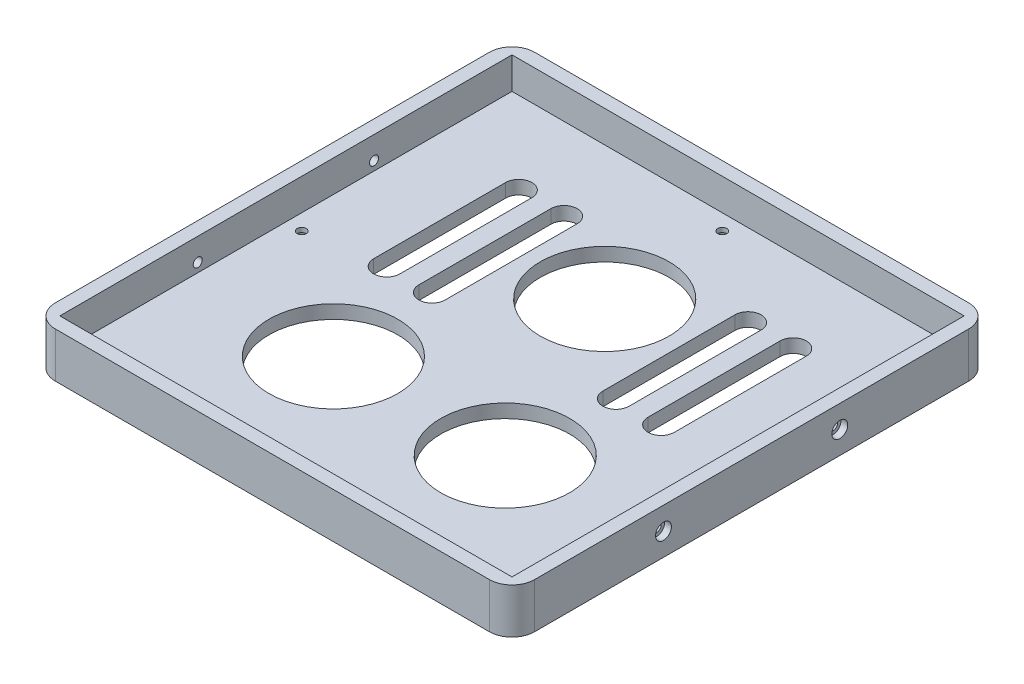
SolidWorks part; units mm, degrees
ref_plane "Front Plane" through (0, 0, 0) normal (0, 0, 1) x (1, 0, 0)
ref_plane "Top Plane" through (0, 0, 0) normal (0, 1, 0) x (1, 0, 0)
ref_plane "Right Plane" through (0, 0, 0) normal (1, 0, 0) x (0, 0, -1)
sketch "Sketch1" plane through (0, 0, 0) normal (0, 1, 0) x (1, 0, 0)
  line L1 (-53, 53) -> (53, 53)
  line L2 (-53, 53) -> (-53, -53)
  line L3 (-53, -53) -> (53, -53)
  line L4 (53, 53) -> (53, -53)
  line L5 (-53, 53) -> (53, -53) construction
  line L6 (-53, -53) -> (53, 53) construction
  point P0 (0, 0)
  dimension "D1" = 106
  dimension "D2" = 106
extrude "Boss-Extrude1" add sketch "Sketch1" along normal blind 10
sketch "Sketch3" plane through (0, 10, 0) normal (0, 1, 0) x (1, 0, 0)
  line L5 (-50, 50) -> (50, 50)
  line L6 (-50, 50) -> (-50, -50)
  line L7 (-50, -50) -> (50, -50)
  line L8 (50, 50) -> (50, -50)
  point P0 (0, 0)
  point P6 (0, 0)
extrude "Cut-Extrude5" cut sketch "Sketch3" against normal blind 7
sketch "Sketch7" plane through (0, 3, 0) normal (0, 1, 0) x (1, 0, 0)
  line L0 (0, 49) -> (0, 20.5) construction
  line L1 (-49, 49) -> (49, 49) construction
  line L2 (-49, 49) -> (-49, -49) construction
  line L3 (-49, -49) -> (49, -49) construction
  line L4 (49, 49) -> (49, -49) construction
  line L5 (0, -49) -> (0, -20.5) construction
  line L6 (49, -20.5) -> (19, -20.5)
  circle A0 centre (0, 20.5) radius 14.25
  circle A1 centre (19, -20.5) radius 14.25
  circle A2 centre (-19, -20.5) radius 14.25
  point P0 (0, 0)
  dimension "D1" = 28.5
  dimension "D2" = 28.5
extrude "Cut-Extrude6" cut sketch "Sketch7" against normal blind 7
sketch "Sketch8" plane through (0, 3, 0) normal (0, 1, 0) x (1, 0, 0)
  line L1 (-49, 49) -> (49, 49) construction
  line L2 (-49, 49) -> (-49, -49) construction
  line L3 (-49, -49) -> (49, -49) construction
  line L4 (49, 49) -> (49, -49) construction
  point P0 (0, 0)
  dimension "D1" = 98
  dimension "D2" = 98
sketch "Sketch9" plane through (0, 0, 0) normal (0, -1, 0) x (1, 0, 0)
  line L0 (0, 49) -> (0, 44) construction
  line L4 (53, -53) -> (53, 53)
  line L5 (53, 53) -> (-53, 53)
  line L6 (-53, 53) -> (-53, -53)
  line L7 (-53, -53) -> (53, -53)
  line L8 (53, -53) -> (53, 53)
  line L9 (53, 53) -> (-53, 53)
  line L10 (-53, 53) -> (-53, -53)
  line L11 (-53, -53) -> (53, -53)
  circle A0 centre (46.5, 0) radius 1.75
  circle A1 centre (0, -46.5) radius 1.75
  circle A2 centre (0, 46.5) radius 1.75
  circle A3 centre (-46.5, 0) radius 1.75
  dimension "D1" = 0
extrude "Cut-Extrude7" cut sketch "Sketch9" against normal blind 2 contours A1 | A3 | A0 | A2
sketch "Sketch11" plane through (0, 2, 0) normal (0, -1, 0) x (1, 0, 0)
  circle A0 centre (46.5, 0) radius 1
  circle A1 centre (0, -46.5) radius 1
  circle A2 centre (-46.5, 0) radius 1
  circle A3 centre (0, 46.5) radius 1
extrude "Cut-Extrude8" cut sketch "Sketch11" against normal blind 17 contours A0 | A1 | A2 | A3
sketch "Sketch12" plane through (53, 0, 0) normal (1, 0, 0) x (0, 0, -1)
  line L0 (-39, 10) -> (-39, 0)
  line L1 (-53, 10) -> (53, 10) construction
  line L2 (-39, 13) -> (-39, 3) construction
  line L3 (-53, 0) -> (53, 0) construction
  line L4 (39, 10) -> (39, 0)
  line L5 (39, 3) -> (39, 13) construction
  line L6 (-39, 10) -> (0, 10)
  line L7 (0, 10) -> (0, 0)
  line L8 (0, 10) -> (39, 10)
  line L9 (-19.5, 10) -> (-19.5, 0)
  line L10 (19.5, 10) -> (19.5, 0)
  circle A0 centre (-19.5, 5) radius 1.75
  circle A1 centre (19.5, 5) radius 1.75
  dimension "D1" = 3.5
extrude "Cut-Extrude9" cut sketch "Sketch12" against normal blind 1.5 contours L9 A0 | A1 L10 | A1 L10
sketch "Sketch14" plane through (51.5, 0, 0) normal (1, 0, 0) x (0, 0, -1)
  circle A0 centre (-19.5, 5) radius 1
  circle A1 centre (19.5, 5) radius 1
extrude "Cut-Extrude10" cut sketch "Sketch14" against normal blind 115.5 contours A0 | A1
sketch "Sketch15" plane through (-53, 0, 0) normal (-1, 0, 0) x (0, 0, 1)
  circle A0 centre (-19.5, 5) radius 1.75
  circle A1 centre (19.5, 5) radius 1.75
  dimension "D1" = 3.5
  dimension "D2" = 3.5
extrude "Cut-Extrude11" cut sketch "Sketch15" against normal blind 1.5 contours A0 | A1
fillet "Fillet1" radius 5 4 edges at (-53, 5, -53) (-53, 5, 53) (53, 5, 53) (53, 5, -53)
sketch "Sketch21" plane through (0, 0, 0) normal (0, -1, 0) x (1, 0, 0)
  line L0 (-23.25, -31.8455) -> (-23.25, -2.6545)
  line L4 (-33.25, -31.8455) -> (-33.25, -2.6545)
  line L6 (-33.25, -31.8455) -> (-33.25, -2.6545)
  line L8 (-27.4411, -31.8455) -> (-27.4411, -2.6545)
  line L9 (-17.4411, -31.8455) -> (-17.4411, -2.6545)
  line L10 (0, -34.75) -> (0, -28.0657)
  line L11 (27.4411, -31.8455) -> (27.4411, -2.6545)
  line L12 (33.25, -31.8455) -> (33.25, -2.6545)
  line L13 (17.4411, -31.8455) -> (17.4411, -2.6545)
  line L14 (23.25, -31.8455) -> (23.25, -2.6545)
  arc A0 (-27.4411, -2.6545) -> (-33.25, -2.6545) centre (-30.3455, -2.6545) ccw
  arc A1 (-33.25, -31.8455) -> (-27.4411, -31.8455) centre (-30.3455, -31.8455) ccw
  arc A2 (-17.4411, -2.6545) -> (-23.25, -2.6545) centre (-20.3455, -2.6545) ccw
  arc A3 (-23.25, -31.8455) -> (-17.4411, -31.8455) centre (-20.3455, -31.8455) ccw
  circle A4 centre (0, -20.5) radius 14.25 construction
  arc A5 (27.4411, -2.6545) -> (33.25, -2.6545) centre (30.3455, -2.6545) cw
  arc A6 (33.25, -31.8455) -> (27.4411, -31.8455) centre (30.3455, -31.8455) cw
  arc A7 (23.25, -31.8455) -> (17.4411, -31.8455) centre (20.3455, -31.8455) cw
  arc A8 (17.4411, -2.6545) -> (23.25, -2.6545) centre (20.3455, -2.6545) cw
  point P0 (0, 0)
  dimension "D1" = 2
extrude "Cut-Extrude12" cut sketch "Sketch21" against normal blind 10 contours L4 A1 L8 A0 | L0 A3 L9 A2 | A6 L12 A5 L11 | L14 A8 L13 A7
